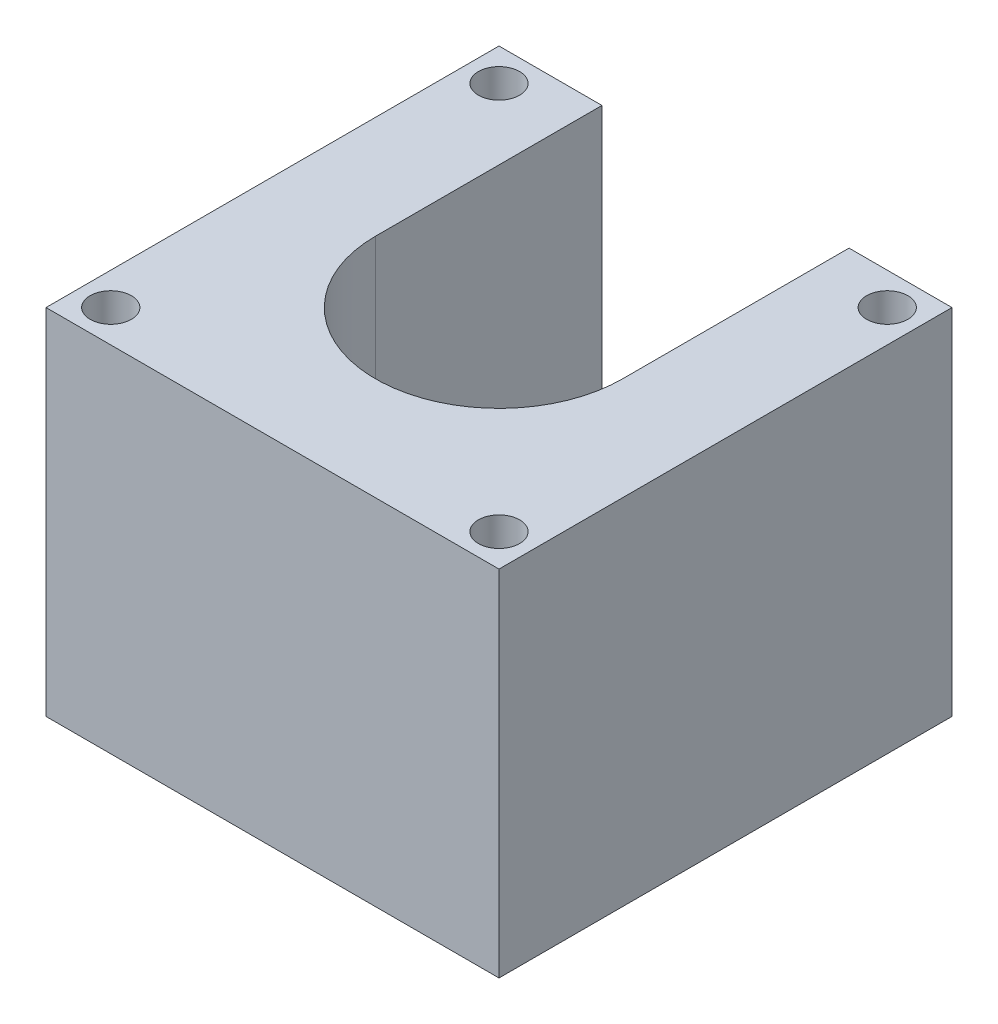
SolidWorks part; units mm, degrees
ref_plane "Front Plane" through (0, 0, 0) normal (0, 0, 1) x (1, 0, 0)
ref_plane "Top Plane" through (0, 0, 0) normal (0, 1, 0) x (1, 0, 0)
ref_plane "Right Plane" through (0, 0, 0) normal (1, 0, 0) x (0, 0, -1)
sketch "Sketch1" plane through (0, 0, 0) normal (0, 1, 0) x (1, 0, 0)
  line L0 (-27.6418, 1.2403) -> (27.3582, 1.2403) construction
  line L1 (-27.6418, 28.7403) -> (27.3582, 28.7403)
  line L2 (-27.6418, 28.7403) -> (-27.6418, -26.2597)
  line L3 (-27.6418, -26.2597) -> (27.3582, -26.2597)
  line L4 (27.3582, 28.7403) -> (27.3582, -26.2597)
  line L5 (-0.1418, -26.2597) -> (-0.1418, 28.7403) construction
  circle A0 centre (-0.1418, 1.2403) radius 15
  dimension "D3" = 30
  dimension "D1" = 55
  dimension "D2" = 55
extrude "Boss-Extrude3" add sketch "Sketch1" along normal blind 9
sketch "Sketch5" plane through (0, 9, 0) normal (0, 1, 0) x (1, 0, 0)
  line L0 (-15.1418, 1.2403) -> (-15.1418, 28.7403)
  line L1 (27.3582, 28.7403) -> (-27.6418, 28.7403) construction
  line L2 (14.8582, 1.2403) -> (14.8582, 28.7403)
  line L3 (-15.1418, 28.7403) -> (-27.6418, 28.7403)
  line L4 (-27.6418, 28.7403) -> (-27.6418, -26.2597)
  line L5 (-27.6418, -26.2597) -> (27.3582, -26.2597)
  line L6 (27.3582, -26.2597) -> (27.3582, 28.7403)
  line L7 (27.3582, 28.7403) -> (14.8582, 28.7403)
  circle A0 centre (-0.1418, 1.2403) radius 15 construction
  circle A1 centre (-0.1418, 1.2403) radius 15
  line M1 (-27.6418, 28.7403) -> (-27.6418, -26.2597)
  line M2 (-27.6418, -26.2597) -> (27.3582, -26.2597)
  line M3 (27.3582, -26.2597) -> (27.3582, 28.7403)
  line M4 (27.3582, 28.7403) -> (-27.6418, 28.7403)
  circle M5 centre (-0.1418, 1.2403) radius 15
extrude "Boss-Extrude4" add sketch "Sketch5" along normal blind 34 contours L2 L0 M5 M4 M1 M2 M3
sketch "Sketch6" plane through (0, 0, 0) normal (0, -1, 0) x (1, 0, 0)
  circle A0 centre (-23.7118, 22.3297) radius 2.5
  circle A1 centre (23.4282, 22.3297) radius 2.5
  circle A2 centre (-23.7118, -24.8103) radius 2.5
  circle A3 centre (23.4282, -24.8103) radius 2.5
  dimension "D1" = 5
  dimension "D2" = 5
  dimension "D3" = 5
  dimension "D4" = 5
extrude "Cut-Extrude1" cut sketch "Sketch6" against normal up to next
